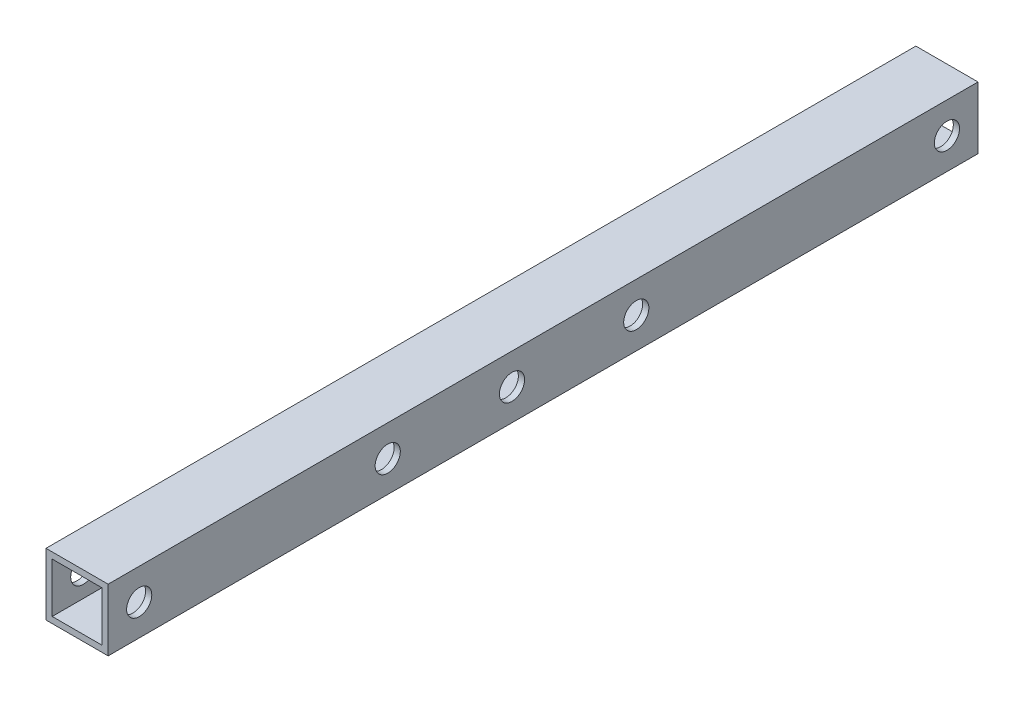
SolidWorks part; units mm, degrees
ref_plane "Front Plane" through (0, 0, 0) normal (0, 0, 1) x (1, 0, 0)
ref_plane "Top Plane" through (0, 0, 0) normal (0, 1, 0) x (1, 0, 0)
ref_plane "Right Plane" through (0, 0, 0) normal (1, 0, 0) x (0, 0, -1)
sketch "Sketch1" plane through (0, 0, 0) normal (0, 0, 1) x (1, 0, 0)
  line L1 (-5, 5) -> (5, 5)
  line L2 (-5, 5) -> (-5, -5)
  line L3 (-5, -5) -> (5, -5)
  line L4 (5, 5) -> (5, -5)
  line L5 (-5, 5) -> (5, -5) construction
  line L6 (-5, -5) -> (5, 5) construction
  line L7 (-4, 4) -> (4, 4)
  line L8 (-4, 4) -> (-4, -4)
  line L9 (-4, -4) -> (4, -4)
  line L10 (4, 4) -> (4, -4)
  line L11 (-4, 4) -> (4, -4) construction
  line L12 (-4, -4) -> (4, 4) construction
  point P0 (0, 0)
  point P6 (0, 0)
  dimension "D1" = 10
  dimension "D2" = 10
  dimension "D3" = 8
  dimension "D4" = 8
extrude "Boss-Extrude1" add sketch "Sketch1" along normal blind 140
sketch "Sketch2" plane through (5, 0, 0) normal (1, 0, 0) x (0, 0, -1)
  line L0 (5.402, 0) -> (-103.3192, 0) construction
  line L1 (0, -5) -> (0, 5) construction
  circle A0 centre (-5, 0) radius 2.025
  dimension "D1" = 4.05
  dimension "D2" = 5
extrude "Cut-Extrude1" cut sketch "Sketch2" against normal through all
sketch "Sketch3" plane through (5, 0, 0) normal (1, 0, 0) x (0, 0, -1)
  line L0 (-141.5353, 0) -> (7.2031, 0) construction
  line L1 (0, -5) -> (0, 5) construction
  circle A0 centre (-75, 0) radius 2.025
  circle A1 centre (-55, 0) radius 2.025
  dimension "D1" = 4.05
  dimension "D2" = 4.05
  dimension "D3" = 20
  dimension "D4" = 55
extrude "Cut-Extrude2" cut sketch "Sketch3" against normal through all
sketch "Sketch4" plane through (5, 0, 0) normal (1, 0, 0) x (0, 0, -1)
  line L0 (-166.3105, 0) -> (7.7545, 0) construction
  line L1 (-140, -5) -> (-140, 5) construction
  circle A4 centre (-135, 0) radius 2.025
  circle A5 centre (-95, 0) radius 2.025
  dimension "D1" = 4.05
  dimension "D2" = 4.05
  dimension "D3" = 40
  dimension "D4" = 5
extrude "Cut-Extrude3" cut sketch "Sketch4" against normal through all
